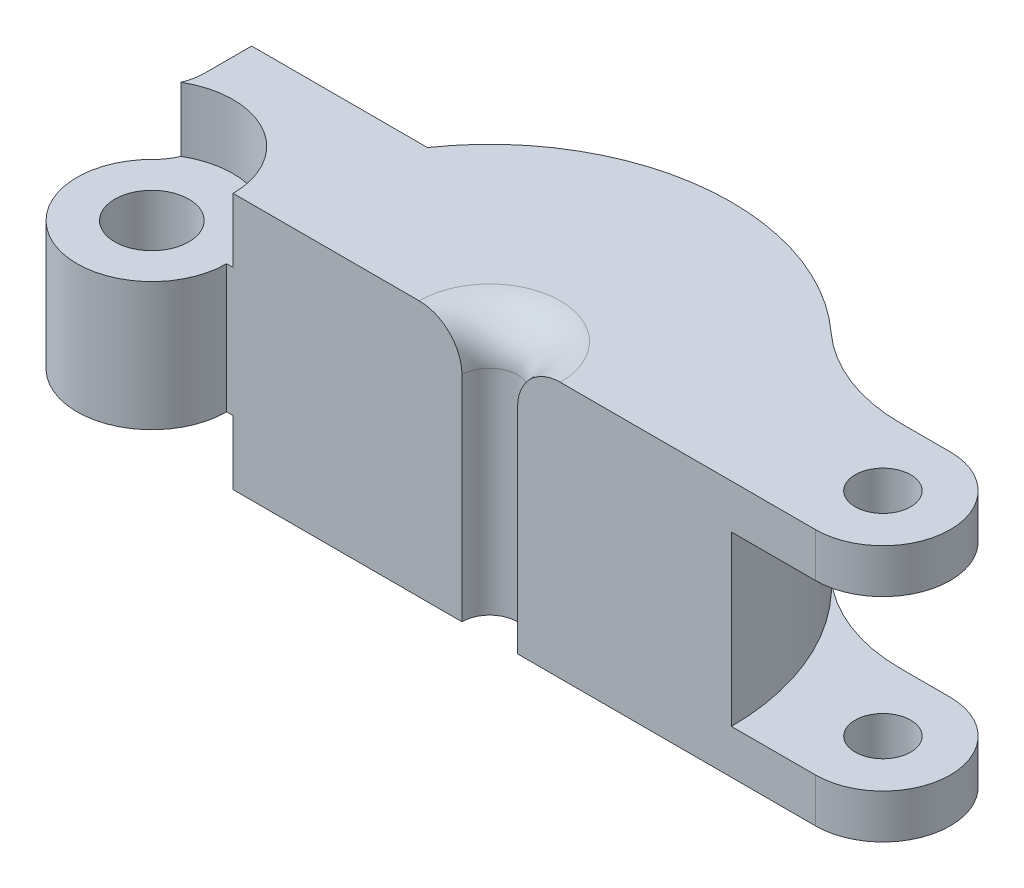
SolidWorks part; units mm, degrees
ref_plane "Front Plane" through (0, 0, 0) normal (0, 0, 1) x (1, 0, 0)
ref_plane "Top Plane" through (0, 0, 0) normal (0, 1, 0) x (1, 0, 0)
ref_plane "Right Plane" through (0, 0, 0) normal (1, 0, 0) x (0, 0, -1)
sketch "Sketch1" plane through (0, 0, 0) normal (0, 1, 0) x (1, 0, 0)
  line L2 (0, 0) -> (0, 14.351) construction
  line L3 (-11.8274, 8.128) -> (-22.27, 8.128)
  line L6 (-22.27, 8.128) -> (-22.27, 3.8624)
  line L7 (14.351, 0) -> (1.651, 0)
  line L10 (14.351, 0) -> (19.351, 0)
  line L11 (-15.625, 0) -> (-1.651, 0)
  line L12 (-20.07, 0) -> (-22.27, 0) construction
  line L13 (19.351, 8) -> (11.9143, 8)
  arc A0 (1.651, 0) -> (-1.651, 0) centre (0, 0) ccw
  arc A1 (11.8274, 8.128) -> (-11.8274, 8.128) centre (0, 0) ccw
  circle A5 centre (-20.07, 0) radius 2.2
  arc A6 (-22.27, 3.8624) -> (-15.625, 0) centre (-20.07, 0) ccw
  arc A7 (11.9143, 8) -> (-11.8274, 8.128) centre (0, 0) ccw
  arc A8 (19.351, 0) -> (19.351, 8) centre (19.351, 4) ccw
  circle A9 centre (19.351, 4) radius 1.65
  point P11 (0, 0)
  point P20 (21.9217, 2.286)
  point P21 (19.2284, 6.1033)
  point P22 (11.4045, 8.7114)
  dimension "D1" = 3.302
  dimension "D2" = 12.7
  dimension "D5" = 4.445
  dimension "D6" = 3.3
  dimension "D7" = 4.4
  dimension "D8" = 8
  dimension "D3" = 20.07
  dimension "D4" = 8.128
  dimension "D9" = 5
  dimension "D10" = 4
  dimension "D11" = 12.7
extrude "Boss-Extrude1" add sketch "Sketch1" along normal blind 15.24 contours L10 A8 L13 A7 A1 L3 L6 A6 L11 A0 L7 A9 A5
ref_plane "Plane1" through (0, 7.62, 0) normal (0, 1, 0) x (1, 0, 0)
sketch "Sketch2" plane through (0, 15.24, 0) normal (0, 1, 0) x (1, 0, 0)
  circle A0 centre (-20.07, 0) radius 4.826
  dimension "D1" = 9.652
extrude "Cut-Extrude1" cut sketch "Sketch2" against normal mid plane 7.62
fillet "Fillet1" [suppressed] radius 2.54
fillet "Fillet2" radius 2.54 1 edges at (0, 15.24, -1.651)
mirror "Mirror1" about plane through (0, 7.62, 0) normal (0, 1, 0) of "Cut-Extrude1"
fillet "Fillet3" radius 3 1 edges at (-22.27, 7.62, -3.8624)
sketch "Sketch3" plane through (0, 7.62, 0) normal (0, 1, 0) x (1, 0, 0)
  line L0 (4.191, 0) -> (19.351, 0) construction
  line L1 (14.351, 0) -> (19.351, 0)
  line L6 (-15.244, 0) -> (-4.191, 0)
  line L7 (4.191, 0) -> (14.351, 0)
  line L9 (19.351, 8) -> (11.9143, 8)
  line L10 (-11.8274, 8.128) -> (-22.27, 8.128)
  line L11 (-22.27, 8.128) -> (-22.27, 5.328)
  line L15 (19.351, 8) -> (11.9143, 8)
  arc A0 (14.351, 0) -> (11.9143, 8) centre (0, 0) ccw
  arc A5 (4.191, 0) -> (-4.191, 0) centre (0, 0) ccw
  arc A6 (19.351, 0) -> (19.351, 8) centre (19.351, 4) ccw
  arc A7 (11.9143, 8) -> (-11.8274, 8.128) centre (0, 0) ccw
  arc A8 (-22.5036, 4.1675) -> (-22.27, 5.328) centre (-25.27, 5.328) ccw
  arc A9 (-15.244, 0) -> (-22.5036, 4.1675) centre (-20.07, 0) ccw
  arc A11 (19.351, 0) -> (19.351, 8) centre (19.351, 4) ccw
  dimension "D1" = 0
extrude "Cut-Extrude2" cut sketch "Sketch3" against normal blind 5 and the other way blind 5
fillet "Fillet4" radius 10 2 edges at (11.9143, 1.31, -8) (11.9143, 13.93, -8)
